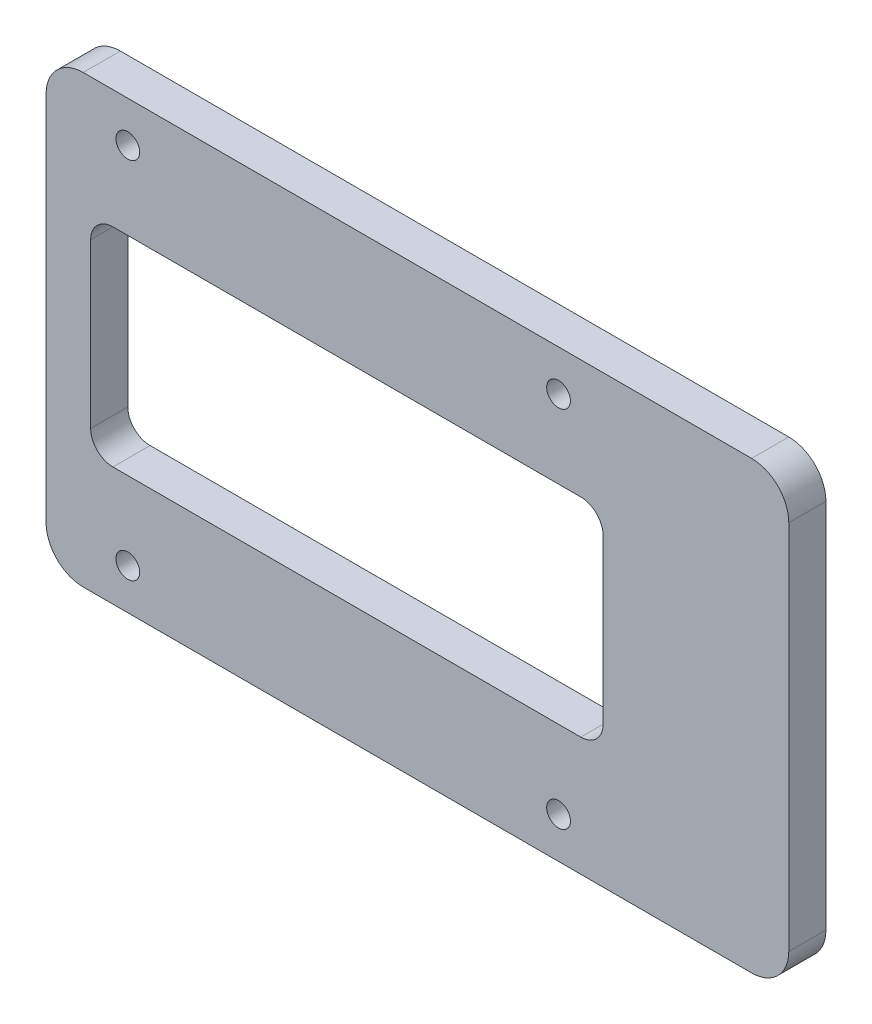
SolidWorks part; units mm, degrees
ref_plane "前视基准面" through (0, 0, 0) normal (0, 0, 1) x (1, 0, 0)
ref_plane "上视基准面" through (0, 0, 0) normal (0, 1, 0) x (1, 0, 0)
ref_plane "右视基准面" through (0, 0, 0) normal (1, 0, 0) x (0, 0, -1)
other "Configuration Table"
sketch "草图1" plane through (0, 0, 0) normal (0, 0, 1) x (1, 0, 0)
  line L0 (-159.4533, 0) -> (191.344, 0) construction
  line L1 (0, 105.0824) -> (0, -113.7085) construction
  line L3 (-45, 30) -> (45, 30)
  line L4 (-50, 25) -> (-50, -25)
  line L5 (-45, -30) -> (45, -30)
  line L6 (50, 25) -> (50, -25)
  line L7 (-41, 14) -> (22, 14)
  line L8 (-44, 11) -> (-44, -11)
  line L9 (-41, -14) -> (22, -14)
  line L10 (25, 11) -> (25, -11)
  circle A0 centre (-39, 24.5) radius 1.6
  circle A1 centre (19, 24.5) radius 1.6
  circle A2 centre (19, -24.5) radius 1.6
  circle A3 centre (-39, -24.5) radius 1.6
  arc A4 (-50, -25) -> (-45, -30) centre (-45, -25) ccw
  arc A5 (45, -30) -> (50, -25) centre (45, -25) ccw
  arc A6 (45, 30) -> (50, 25) centre (45, 25) cw
  arc A7 (-45, 30) -> (-50, 25) centre (-45, 25) ccw
  arc A8 (22, -14) -> (25, -11) centre (22, -11) ccw
  arc A9 (-44, -11) -> (-41, -14) centre (-41, -11) ccw
  arc A10 (22, 14) -> (25, 11) centre (22, 11) cw
  arc A11 (-41, 14) -> (-44, 11) centre (-41, 11) ccw
  dimension "D1" = 5
  dimension "D2" = 3
extrude "凸台-拉伸1" add sketch "草图1" along normal blind 5
